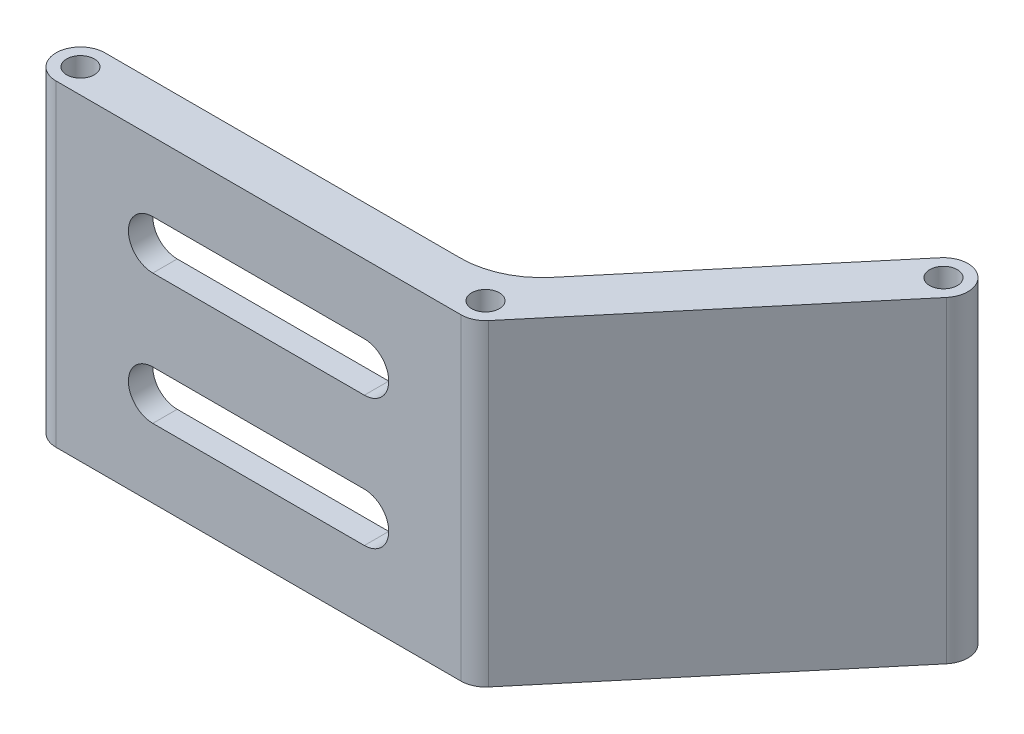
SolidWorks part; units mm, degrees
ref_plane "前视基准面" through (0, 0, 0) normal (0, 0, 1) x (1, 0, 0)
ref_plane "上视基准面" through (0, 0, 0) normal (0, 1, 0) x (1, 0, 0)
ref_plane "右视基准面" through (0, 0, 0) normal (1, 0, 0) x (0, 0, -1)
sketch "草图1" plane through (0, 0, 0) normal (0, 1, 0) x (1, 0, 0)
  line L0 (-24.2143, 0) -> (33.9857, 0) construction
  line L1 (0, 21.7286) -> (0, -22.0714) construction
  line L2 (-14.2777, -3) -> (35.5055, -3)
  line L5 (-11.2777, 0) -> (32.5055, 0)
  line L6 (35.5055, 0) -> (70.0693, 41.1916) construction
  line L7 (37.8036, -1.9284) -> (63.497, 28.6919)
  line L8 (37.4338, 2.2981) -> (61.1989, 30.6202)
  line L9 (61.1989, 30.6202) -> (63.497, 28.6919)
  line L10 (62.5642, 32.2474) -> (14.9363, -24.5134) construction
  line L11 (-14.2777, 0) -> (14.9363, -24.5134) construction
  circle A6 centre (-14.2777, 0) radius 1.7
  circle A7 centre (35.5055, 0) radius 1.7
  arc A8 (-11.2777, 0) -> (-14.2777, -3) centre (-14.2777, 0) ccw
  arc A9 (35.5055, -3) -> (37.8036, -1.9284) centre (35.5055, 0) ccw
  arc A11 (37.4338, 2.2981) -> (32.5055, 0) centre (35.5055, 0) ccw
  arc A12 (37.8036, -1.9284) -> (37.4338, 2.2981) centre (35.5055, 0) ccw construction
  dimension "D1" = 3.4
  dimension "D2" = 3.4
  dimension "D3" = 6
  dimension "D4" = 6
  dimension "D5" = 32
  dimension "D6" = 50
  dimension "D7" = 30.6202
extrude "凸台-拉伸1" add sketch "草图1" along normal blind 39
fillet "圆角1" radius 10 3 edges at (37.4338, 19.5, -2.2981) (32.5055, 19.5, 0) (-11.2777, 19.5, 0)
sketch "草图3" plane through (0, 0, 0) normal (0, 1, 0) x (1, 0, 0)
  line L0 (-14.2777, 0) -> (35.5055, 0) construction
  line L1 (-14.2777, 3) -> (35.5055, 3)
  line L2 (-14.2777, -3) -> (35.5055, -3)
  arc A0 (-14.2777, 3) -> (-14.2777, -3) centre (-14.2777, 0) ccw
  arc A1 (35.5055, -3) -> (35.5055, 3) centre (35.5055, 0) ccw
  circle A2 centre (35.5055, 0) radius 1.7
  point P4 (10.6139, 0)
  dimension "D1" = 3
extrude "凸台-拉伸2" add sketch "草图3" along normal blind 5
sketch "草图4" plane through (0, 39, 0) normal (0, 1, 0) x (1, 0, 0)
  line L0 (-14.2777, 0) -> (35.5055, 0) construction
  line L1 (-14.2777, 3) -> (35.5055, 3)
  line L2 (-14.2777, -3) -> (35.5055, -3)
  arc A0 (-14.2777, 3) -> (-14.2777, -3) centre (-14.2777, 0) ccw
  arc A1 (35.5055, -3) -> (35.5055, 3) centre (35.5055, 0) ccw
  circle A2 centre (-14.2777, 0) radius 1.7
  circle A3 centre (35.5055, 0) radius 1.7
  point P4 (10.6139, 0)
  dimension "D1" = 3
extrude "凸台-拉伸3" add sketch "草图4" against normal blind 3
sketch "草图5" plane through (0, 0, 3) normal (0, 0, 1) x (1, 0, 0)
  line L0 (-17.2777, 19.5) -> (37.8036, 19.5) construction
  line L1 (-17.2777, 39) -> (-17.2777, 0) construction
  line L2 (37.8036, 39) -> (37.8036, 0) construction
  line L3 (10.6139, 39) -> (10.6139, 0) construction
  line L4 (-14.2777, 39) -> (35.5055, 39) construction
  line L5 (-14.2777, 0) -> (35.5055, 0) construction
  line L6 (-2.3861, 27.5) -> (23.6139, 27.5) construction
  line L7 (-2.3861, 30.5) -> (23.6139, 30.5)
  line L8 (-2.3861, 24.5) -> (23.6139, 24.5)
  line L9 (-2.3861, 11.5) -> (23.6139, 11.5) construction
  line L10 (-2.3861, 8.5) -> (23.6139, 8.5)
  line L11 (-2.3861, 14.5) -> (23.6139, 14.5)
  arc A0 (-2.3861, 30.5) -> (-2.3861, 24.5) centre (-2.3861, 27.5) ccw
  arc A1 (23.6139, 24.5) -> (23.6139, 30.5) centre (23.6139, 27.5) ccw
  arc A2 (-2.3861, 8.5) -> (-2.3861, 14.5) centre (-2.3861, 11.5) cw
  arc A3 (23.6139, 14.5) -> (23.6139, 8.5) centre (23.6139, 11.5) cw
  point P14 (10.6139, 27.5)
  point P21 (10.6139, 11.5)
  dimension "D1" = 3
  dimension "D2" = 26
  dimension "D3" = 8
extrude "切除-拉伸2" cut sketch "草图5" against normal blind 5
sketch "草图6" plane through (0, 39, 0) normal (0, 1, 0) x (1, 0, 0)
  line L0 (35.5055, 0) -> (61.1885, 30.6079) construction
  line L1 (61.1989, 30.6202) -> (40.8449, 6.3632) construction
  line L2 (35.5055, 0) -> (61.1885, 30.6079) construction
  line L3 (33.2073, 1.9284) -> (58.8904, 32.5362)
  line L4 (37.8036, -1.9284) -> (63.4867, 28.6795)
  arc A0 (33.2073, 1.9284) -> (37.8036, -1.9284) centre (35.5055, 0) ccw
  arc A1 (63.4867, 28.6795) -> (58.8904, 32.5362) centre (61.1885, 30.6079) ccw
  circle A2 centre (35.5055, 0) radius 1.7
  circle A3 centre (61.1885, 30.6079) radius 1.7
  point P7 (48.347, 15.3039)
  dimension "D1" = 3
  dimension "D2" = 3.4
extrude "凸台-拉伸4" add sketch "草图6" against normal blind 3
sketch "草图7" plane through (0, 0, 0) normal (0, 1, 0) x (1, 0, 0)
  line L0 (35.5055, 0) -> (61.1885, 30.6079) construction
  line L1 (33.2073, 1.9284) -> (58.8904, 32.5362)
  line L2 (37.8036, -1.9284) -> (63.4867, 28.6795)
  arc A0 (33.2073, 1.9284) -> (37.8036, -1.9284) centre (35.5055, 0) ccw
  arc A1 (63.4867, 28.6795) -> (58.8904, 32.5362) centre (61.1885, 30.6079) ccw
  circle A2 centre (35.5055, 0) radius 1.7
  circle A3 centre (61.1885, 30.6079) radius 1.7
  point P4 (48.347, 15.3039)
  dimension "D1" = 3
extrude "凸台-拉伸5" add sketch "草图7" along normal blind 5
sketch "草图8" plane through (0, 0, 0) normal (0, 1, 0) x (1, 0, 0)
  circle A0 centre (61.1885, 30.6079) radius 3
  circle A1 centre (61.1885, 30.6079) radius 1.7
extrude "凸台-拉伸6" add sketch "草图8" along normal blind 39
sketch "草图9" plane through (0, 0, 0) normal (0, 1, 0) x (1, 0, 0)
  circle A0 centre (61.1885, 30.6079) radius 1.7
extrude "切除-拉伸3" cut sketch "草图9" along normal blind 100 contours A0
fillet "圆角2" radius 10 2 edges at (34.1065, 37.5, -3) (34.1065, 2.5, -3)
